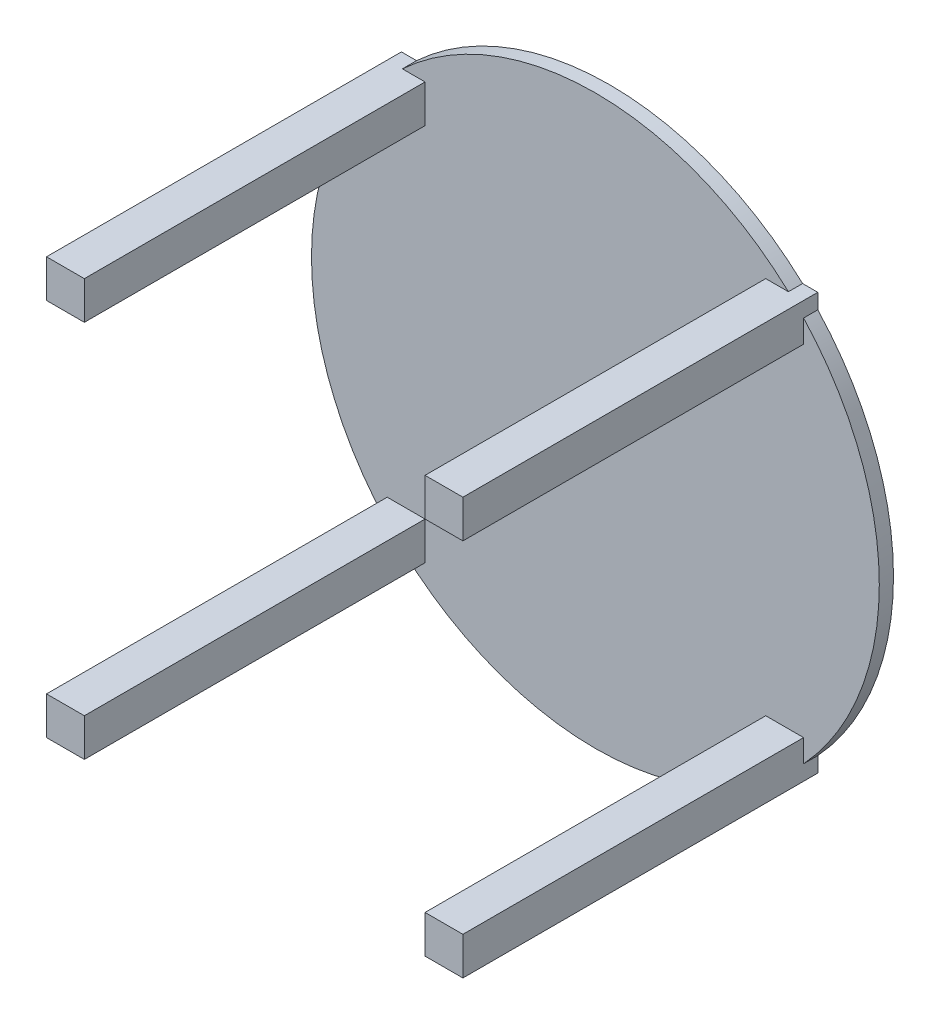
SolidWorks part; units mm, degrees
ref_plane "前视基准面" through (0, 0, 0) normal (0, 0, 1) x (1, 0, 0)
ref_plane "上视基准面" through (0, 0, 0) normal (0, 1, 0) x (1, 0, 0)
ref_plane "右视基准面" through (0, 0, 0) normal (1, 0, 0) x (0, 0, -1)
other "Configuration Table"
sketch "草图1" plane through (0, 0, 0) normal (0, 0, 1) x (1, 0, 0)
  circle A0 centre (0, 0) radius 600
extrude "凸台-拉伸1" add sketch "草图1" along normal blind 30
sketch "草图2" plane through (0, 0, 0) normal (0, 0, 1) x (1, 0, 0)
  line L1 (-440, -440) -> (-360, -440)
  line L2 (-440, -440) -> (-440, -360)
  line L3 (-440, -360) -> (-360, -360)
  line L4 (-360, -440) -> (-360, -360)
  line L5 (-440, -440) -> (-360, -360) construction
  line L6 (-440, -360) -> (-360, -440) construction
  point P0 (-400, -400)
extrude "凸台-拉伸2" add sketch "草图2" along normal blind 750
sketch "草图3" plane through (0, 0, 0) normal (0, 0, 1) x (1, 0, 0)
  line L1 (360, -440) -> (440, -440)
  line L2 (360, -440) -> (360, -360)
  line L3 (360, -360) -> (440, -360)
  line L4 (440, -440) -> (440, -360)
  line L5 (360, -440) -> (440, -360) construction
  line L6 (360, -360) -> (440, -440) construction
  point P0 (400, -400)
extrude "凸台-拉伸3" add sketch "草图3" along normal blind 750
sketch "草图4" plane through (0, 0, 0) normal (0, 0, 1) x (1, 0, 0)
  line L1 (-440, 360) -> (-360, 360)
  line L2 (-440, 360) -> (-440, 440)
  line L3 (-440, 440) -> (-360, 440)
  line L4 (-360, 360) -> (-360, 440)
  line L5 (-440, 360) -> (-360, 440) construction
  line L6 (-440, 440) -> (-360, 360) construction
  point P0 (-400, 400)
extrude "凸台-拉伸4" add sketch "草图4" along normal blind 750
sketch "草图5" plane through (0, 0, 0) normal (0, 0, 1) x (1, 0, 0)
  line L1 (360, 360) -> (440, 360)
  line L2 (360, 360) -> (360, 440)
  line L3 (360, 440) -> (440, 440)
  line L4 (440, 360) -> (440, 440)
  line L5 (360, 360) -> (440, 440) construction
  line L6 (360, 440) -> (440, 360) construction
  point P0 (400, 400)
extrude "凸台-拉伸5" add sketch "草图5" along normal blind 750
